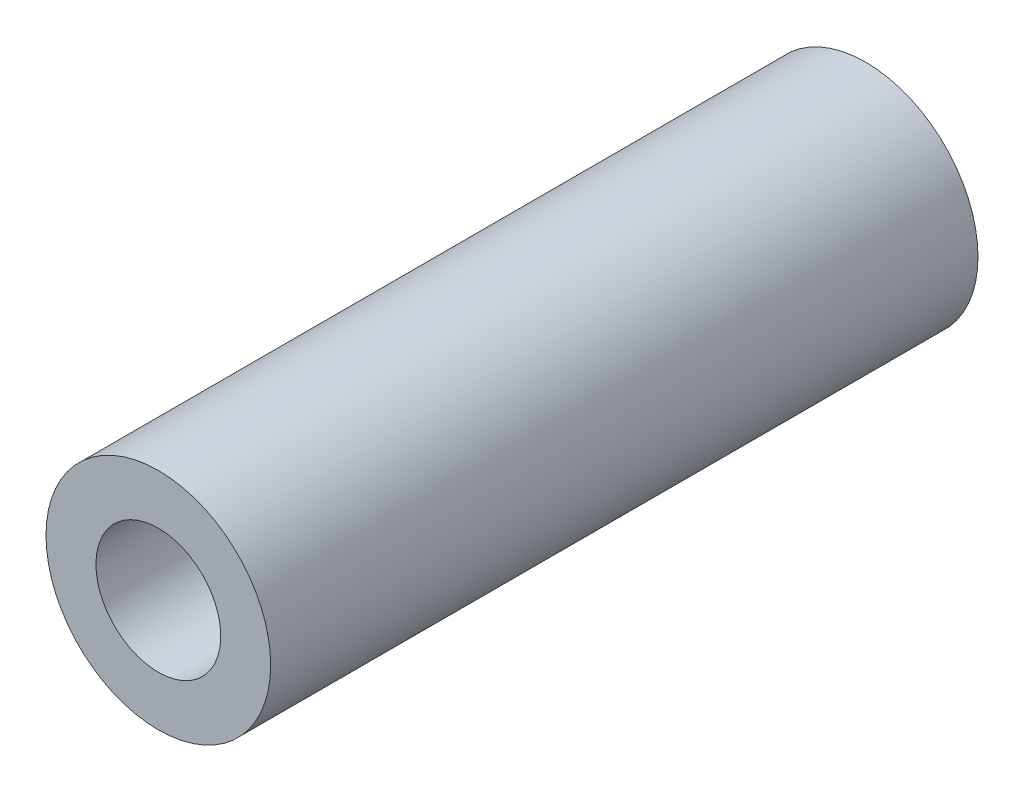
SolidWorks part; units mm, degrees
material "Rubber"
ref_plane "Front Plane" through (0, 0, 0) normal (0, 0, 1) x (1, 0, 0)
ref_plane "Top Plane" through (0, 0, 0) normal (0, 1, 0) x (1, 0, 0)
ref_plane "Right Plane" through (0, 0, 0) normal (1, 0, 0) x (0, 0, -1)
sketch "Sketch1" plane through (0, 0, 0) normal (1, 0, 0) x (0, 0, -1)
  line L0 (53.975, 0) -> (-53.975, 0) construction
  line L1 (53.975, 9.525) -> (53.975, -9.525) construction
  line L2 (53.975, 9.525) -> (53.975, 17.145) construction
  dimension "Length" = 107.95
  dimension "For OD" = 19.05
  dimension "Material Thickness" = 7.62
sketch "Sketch5" plane through (0, 0, 0) normal (1, 0, 0) x (0, 0, -1)
  line L0 (53.975, 0) -> (-53.975, 0) construction
  line L1 (53.975, 9.525) -> (53.975, -9.525) construction
  line L2 (53.975, 9.525) -> (53.975, 17.145) construction
  line L3 (53.975, 9.525) -> (53.975, 17.145)
  line L4 (53.975, 17.145) -> (-53.975, 17.145)
  line L5 (-53.975, 17.145) -> (-53.975, 9.525)
  line L6 (-53.975, 9.525) -> (53.975, 9.525)
  line L7 (53.975, 0) -> (-53.975, 0) construction
revolve "Revolve1" add sketch "Sketch5" angle 360 about L0
sketch "Sketch2" plane through (0, 0, 0) normal (1, 0, 0) x (0, 0, -1)
  line L0 (-53.975, 0) -> (-2.54, 0) construction
  line L1 (53.975, 0) -> (-53.975, 0) construction
  line L2 (53.975, 0) -> (2.54, 0) construction
  dimension "D1" = 51.435
sketch "Sketch3" plane through (0, 0, 53.975) normal (0, 0, 1) x (1, 0, 0)
  line L0 (9.525, 0) -> (17.145, 0) construction
  circle A0 centre (0, 0) radius 9.525 construction
  circle A1 centre (0, 0) radius 17.145 construction
equation "\"D1@Sketch2\" =  ( \"Material Thickness@Sketch1\" + \"For OD@Sketch1\" + \"Material Thickness@Sketch1\" )  * 1.5"
